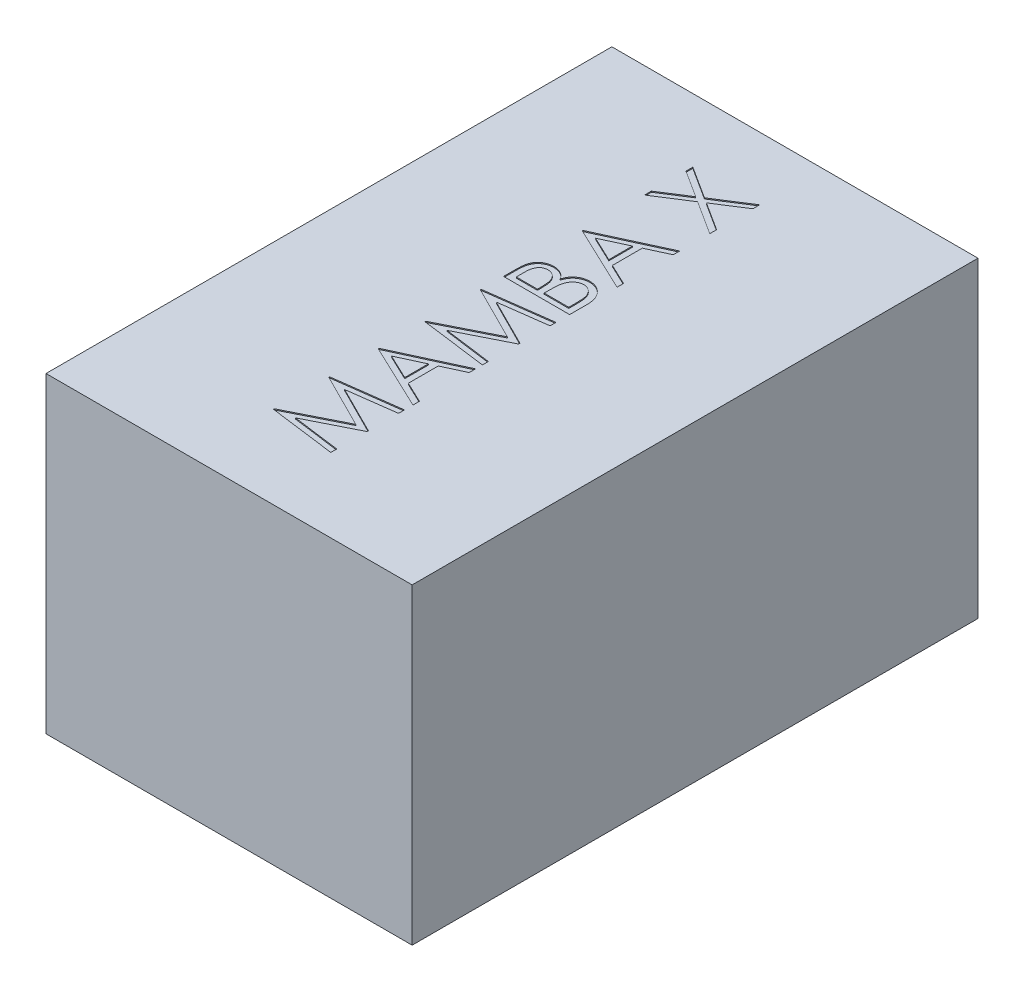
SolidWorks part; units mm, degrees
ref_plane "Front" through (0, 0, 0) normal (0, 0, 1) x (1, 0, 0)
ref_plane "Top" through (0, 0, 0) normal (0, 1, 0) x (1, 0, 0)
ref_plane "Right" through (0, 0, 0) normal (1, 0, 0) x (0, 0, -1)
sketch "Sketch1" plane through (0, 0, 0) normal (0, 1, 0) x (1, 0, 0)
  line L1 (17.6, -27.2) -> (-17.6, -27.2)
  line L2 (17.6, -27.2) -> (17.6, 27.2)
  line L3 (17.6, 27.2) -> (-17.6, 27.2)
  line L4 (-17.6, -27.2) -> (-17.6, 27.2)
  line L5 (17.6, -27.2) -> (-17.6, 27.2) construction
  line L6 (17.6, 27.2) -> (-17.6, -27.2) construction
  point P0 (0, 0)
  dimension "D1" = 54.4
  dimension "D2" = 35.2
extrude "Boss-Extrude1" add sketch "Sketch1" along normal blind 30
sketch "Sketch2" plane through (0, 30, 0) normal (0, 1, 0) x (1, 0, 0)
  line L0 (2.6637, -20.5718) -> (2.6637, 23.5766) construction
  text T0 "MAMBA X"
extrude "Cut-Extrude1" cut sketch "Sketch2" against normal blind 0.1
